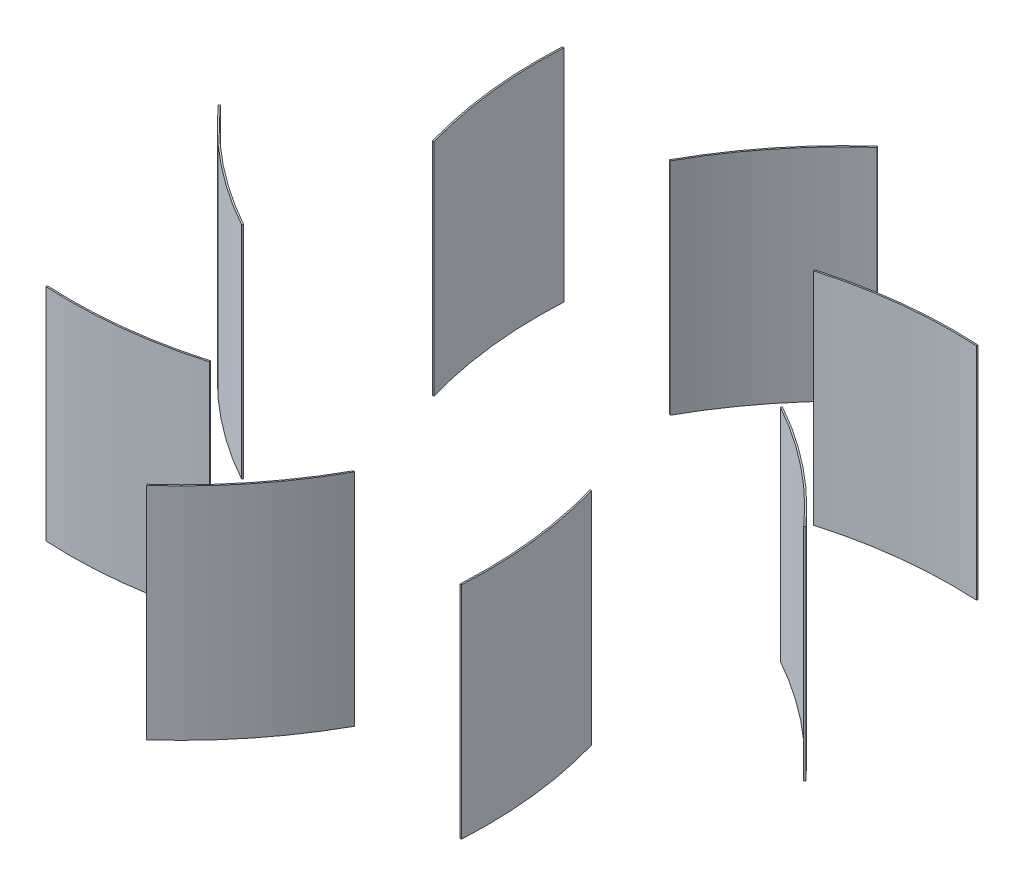
SolidWorks part; units mm, degrees
ref_plane "Front Plane" through (0, 0, 0) normal (0, 0, 1) x (1, 0, 0)
ref_plane "Top Plane" through (0, 0, 0) normal (0, 1, 0) x (1, 0, 0)
ref_plane "Right Plane" through (0, 0, 0) normal (1, 0, 0) x (0, 0, -1)
ref_plane "Plane1" through (0, 1200, 0) normal (0, 1, 0) x (1, 0, 0)
sketch "Sketch1" plane through (0, 1200, 0) normal (0, 1, 0) x (1, 0, 0)
  arc A13 (50, 447.2136) -> (-75, 290.4738) centre (450, 0) ccw
  arc A14 (351.5831, 280.8724) -> (152.363, 258.429) centre (318.1981, -318.1981) ccw
  arc A15 (447.2136, -50) -> (290.4738, 75) centre (0, -450) ccw
  arc A18 (280.8724, -351.5831) -> (258.429, -152.363) centre (-318.1981, -318.1981) ccw
  arc A19 (-50, -447.2136) -> (75, -290.4738) centre (-450, 0) ccw
  arc A21 (-351.5831, -280.8724) -> (-152.363, -258.429) centre (-318.1981, 318.1981) ccw
  arc A22 (-447.2136, 50) -> (-290.4738, -75) centre (0, 450) ccw
  arc A23 (-280.8724, 351.5831) -> (-258.429, 152.363) centre (318.1981, 318.1981) ccw
extrude "Extrude-Thin3" add sketch "Sketch1" along normal blind 300 thin
